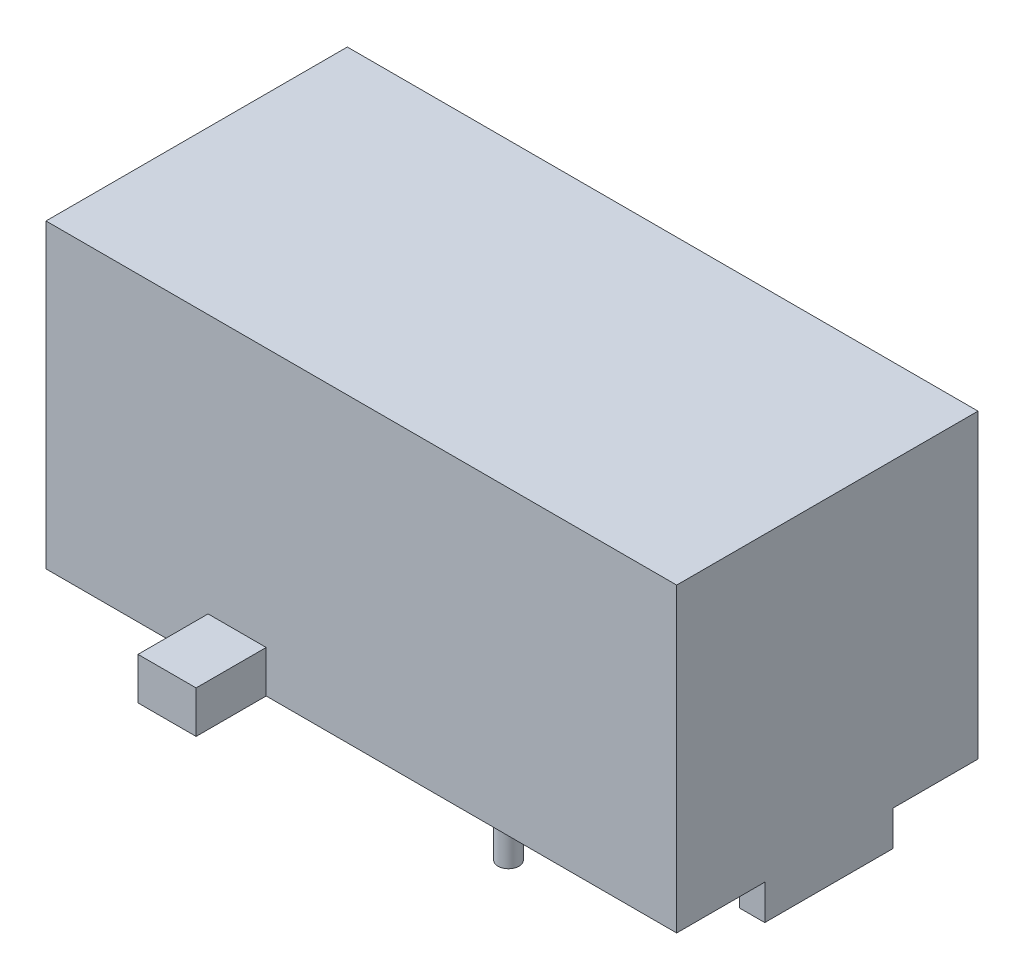
SolidWorks part; units mm, degrees
ref_plane "前视基准面" through (0, 0, 0) normal (0, 0, 1) x (1, 0, 0)
ref_plane "上视基准面" through (0, 0, 0) normal (0, 1, 0) x (1, 0, 0)
ref_plane "右视基准面" through (0, 0, 0) normal (1, 0, 0) x (0, 0, -1)
sketch "草图1" plane through (0, 0, 0) normal (1, 0, 0) x (0, 0, -1)
  line L1 (0, 0) -> (-43, 0)
  line L2 (0, 0) -> (0, 43)
  line L3 (0, 43) -> (-43, 43)
  line L4 (-43, 0) -> (-43, 43)
extrude "凸台-拉伸1" add sketch "草图1" along normal blind 90
sketch "草图2" plane through (0, 0, 0) normal (0, -1, 0) x (1, 0, 0)
  line L0 (90, 43) -> (90, 0) construction
  line L1 (90, 0) -> (0, 0) construction
  circle A0 centre (40, 17) radius 1.5
  dimension "D1" = 3
  dimension "D2" = 50
  dimension "D3" = 17
extrude "凸台-拉伸2" add sketch "草图2" along normal blind 29
sketch "草图3" plane through (0, 0, 0) normal (0, -1, 0) x (1, 0, 0)
  line L0 (90, 43) -> (90, 0) construction
  line L1 (90, 30.4299) -> (86.4006, 30.4299)
  line L2 (90, 30.4299) -> (90, 12.103)
  line L3 (90, 12.103) -> (86.4006, 12.103)
  line L4 (86.4006, 30.4299) -> (86.4006, 12.103)
extrude "凸台-拉伸3" add sketch "草图3" along normal blind 5
sketch "草图4" plane through (0, 0, 43) normal (0, 0, 1) x (1, 0, 0)
  line L0 (90, 0) -> (0, 0) construction
  line L1 (23.1284, 0) -> (31.4202, 0)
  line L2 (23.1284, 0) -> (23.1284, 6.0019)
  line L3 (23.1284, 6.0019) -> (31.4202, 6.0019)
  line L4 (31.4202, 0) -> (31.4202, 6.0019)
extrude "凸台-拉伸4" add sketch "草图4" along normal blind 10
